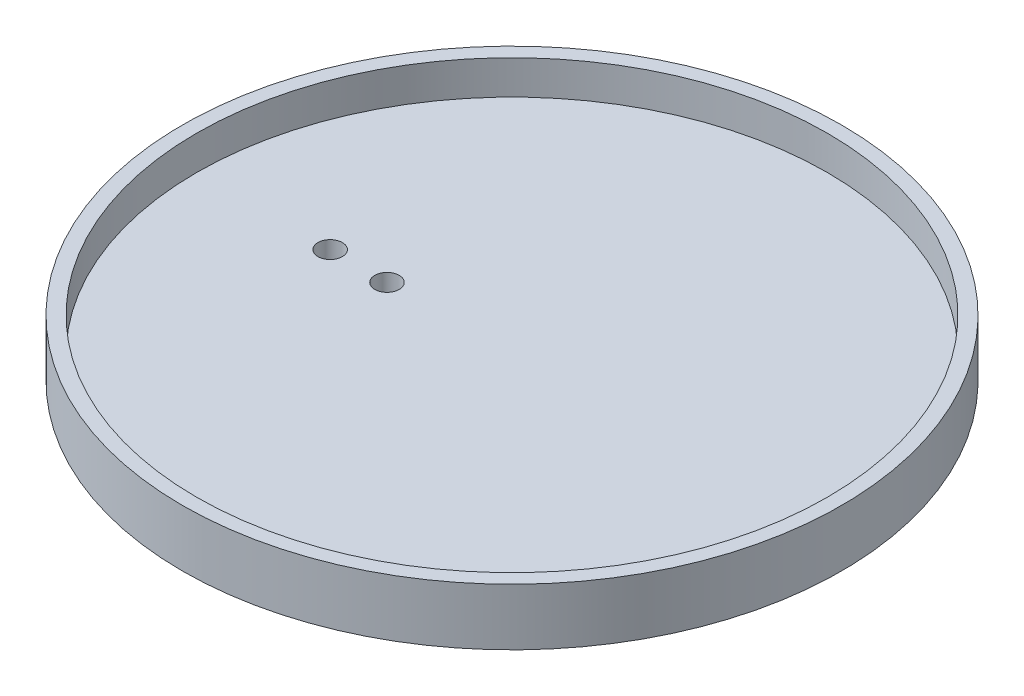
SolidWorks part; units mm, degrees
ref_plane "前视基准面" through (0, 0, 0) normal (0, 0, 1) x (1, 0, 0)
ref_plane "上视基准面" through (0, 0, 0) normal (0, 1, 0) x (1, 0, 0)
ref_plane "右视基准面" through (0, 0, 0) normal (1, 0, 0) x (0, 0, -1)
other "Configuration Table"
sketch "草图1" plane through (0, 0, 0) normal (0, 1, 0) x (1, 0, 0)
  circle A0 centre (0, 0) radius 58
extrude "Cup_plate_D116_T4" add sketch "草图1" along normal blind 4
sketch "草图2" plane through (0, 0, 0) normal (0, 1, 0) x (1, 0, 0)
  circle A0 centre (0, 0) radius 58
  circle A1 centre (0, 0) radius 55.5
extrude "Drip_skirt_OD116_ID111_H10" add sketch "草图2" along normal blind 10
sketch "草图3" plane through (0, 0, 0) normal (0, 1, 0) x (1, 0, 0)
  circle A0 centre (-22, 0) radius 2.15
  circle A1 centre (-32, 0) radius 2.15
extrude "M4_moving_mount_clearance" cut sketch "草图3" along normal blind 4
